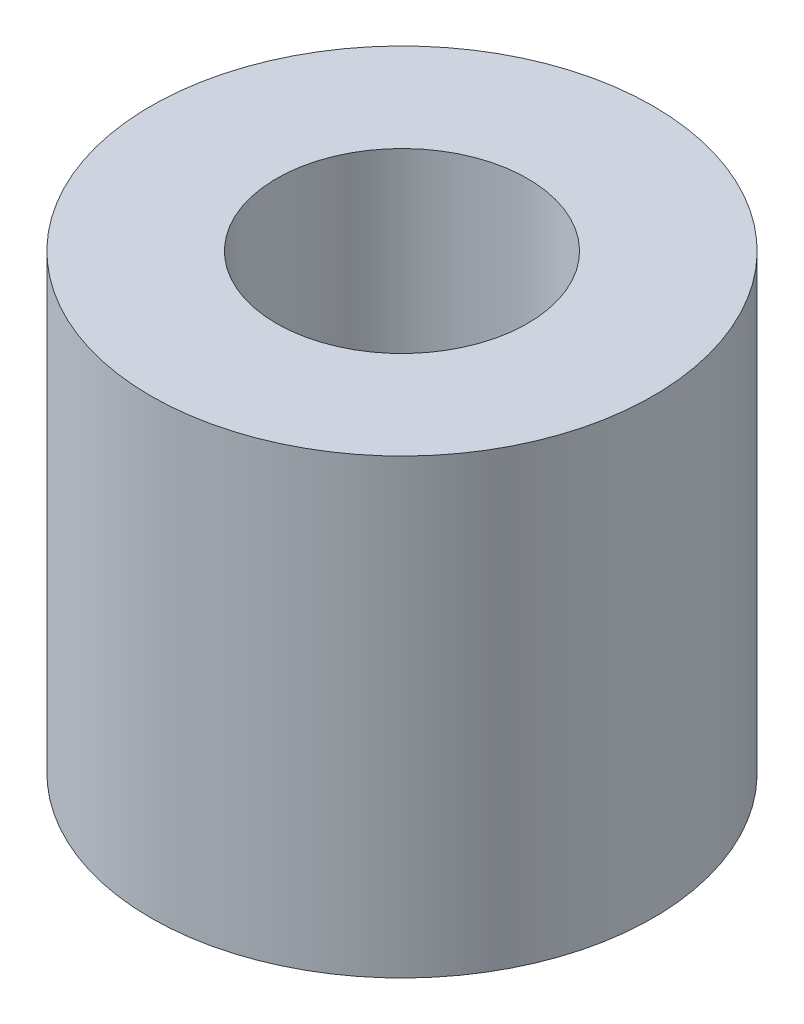
SolidWorks part; units mm, degrees
ref_plane "Front Plane" through (0, 0, 0) normal (0, 0, 1) x (1, 0, 0)
ref_plane "Top Plane" through (0, 0, 0) normal (0, 1, 0) x (1, 0, 0)
ref_plane "Right Plane" through (0, 0, 0) normal (1, 0, 0) x (0, 0, -1)
sketch "Sketch1" plane through (0, 0, 0) normal (0, 1, 0) x (1, 0, 0)
  circle A0 centre (0, 0) radius 2.5
  circle A1 centre (0, 0) radius 5
  dimension "D1" = 5
  dimension "D2" = 10
extrude "Boss-Extrude1" add sketch "Sketch1" along normal blind 9
